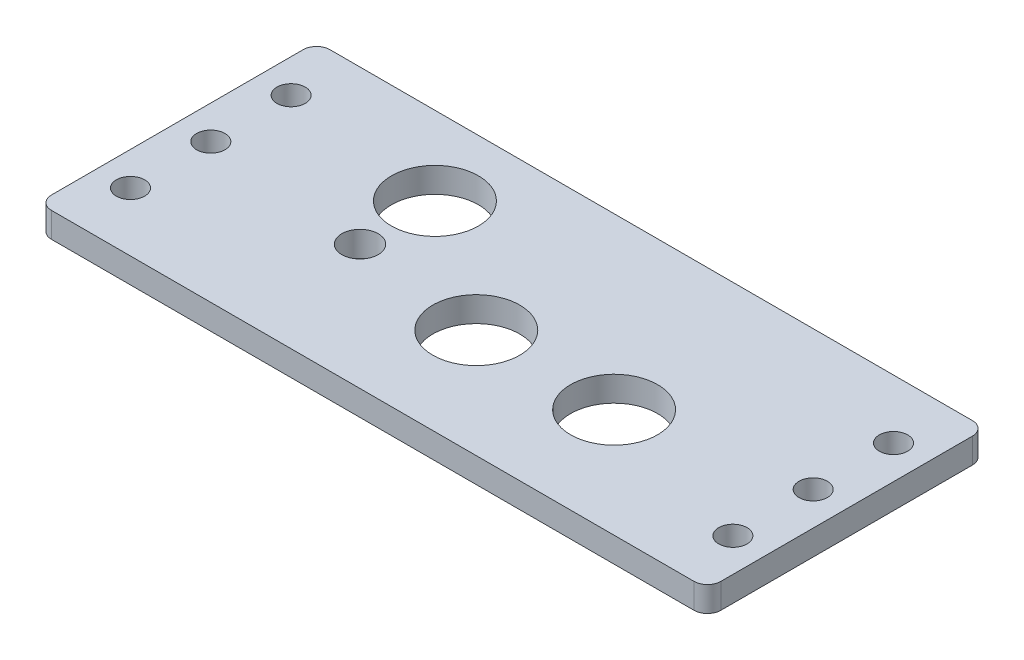
SolidWorks part; units mm, degrees
material "PE High Density Film"
ref_plane "Front Plane" through (0, 0, 0) normal (0, 0, 1) x (1, 0, 0)
ref_plane "Top Plane" through (0, 0, 0) normal (0, 1, 0) x (1, 0, 0)
ref_plane "Right Plane" through (0, 0, 0) normal (1, 0, 0) x (0, 0, -1)
sketch "Sketch1" plane through (0, 0, 0) normal (0, 1, 0) x (1, 0, 0)
  line L1 (-63.5, 26.416) -> (63.5, 26.416)
  line L2 (-63.5, 26.416) -> (-63.5, -26.416)
  line L3 (-63.5, -26.416) -> (63.5, -26.416)
  line L4 (63.5, 26.416) -> (63.5, -26.416)
  line L5 (-63.5, 26.416) -> (63.5, -26.416) construction
  line L6 (-63.5, -26.416) -> (63.5, 26.416) construction
  point P0 (0, 0)
  dimension "D1" = 127
  dimension "D2" = 52.832
extrude "Boss-Extrude1" add sketch "Sketch1" along normal blind 4.7625
fillet "Fillet1" radius 2.54 4 edges at (63.5, 2.3813, 26.416) (63.5, 2.3813, -26.416) (-63.5, 2.3813, -26.416) (-63.5, 2.3813, 26.416)
sketch "Sketch2" plane through (0, 0, 0) normal (0, -1, 0) x (1, 0, 0)
  line L4 (-60.96, 26.416) -> (60.96, 26.416) construction
  circle A0 centre (57.15, -15.24) radius 2.69
  circle A1 centre (57.15, 0) radius 2.69
  circle A2 centre (57.15, 15.24) radius 2.69
  dimension "D1" = 5.38
  dimension "D2" = 11.176
  dimension "D3" = 15.24
  dimension "D4" = 15.24
extrude "Cut-Extrude1" cut sketch "Sketch2" against normal through all
mirror "Mirror1" about plane through (0, 0, 0) normal (1, 0, 0) of "Cut-Extrude1"
sketch "Sketch3" plane through (0, 4.7625, 0) normal (0, 1, 0) x (1, 0, 0)
  circle A0 centre (25.1643, -5.7912) radius 8.25
  circle A1 centre (-0.9857, -5.7912) radius 8.25
extrude "Cut-Extrude2" cut sketch "Sketch3" against normal through all
sketch "Sketch4" plane through (0, 4.7625, 0) normal (0, 1, 0) x (1, 0, 0)
  circle A0 centre (-26.1437, 11.5226) radius 8.255
  circle A1 centre (-26.1437, -2.6959) radius 3.4505
  dimension "D1" = 16.51
extrude "Cut-Extrude3" cut sketch "Sketch4" against normal through all
